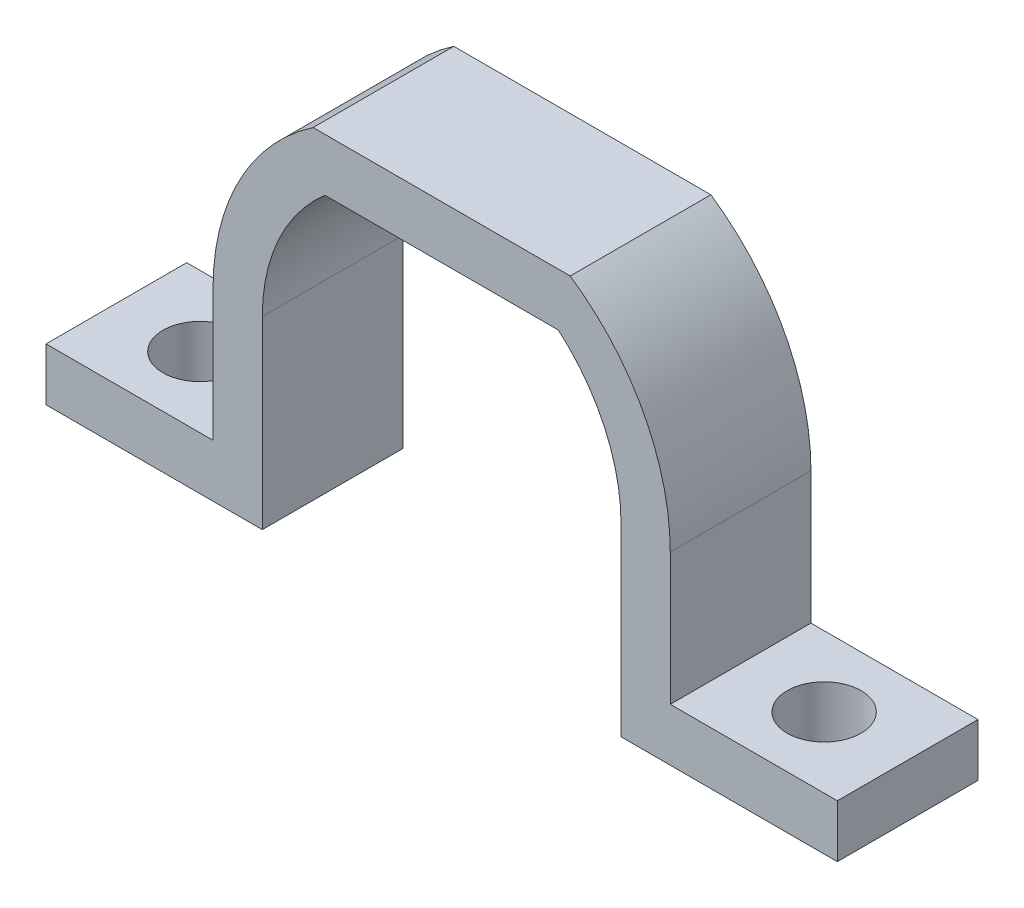
SolidWorks part; units mm, degrees
ref_plane "Front Plane" through (0, 0, 0) normal (0, 0, 1) x (1, 0, 0)
ref_plane "Top Plane" through (0, 0, 0) normal (0, 1, 0) x (1, 0, 0)
ref_plane "Right Plane" through (0, 0, 0) normal (1, 0, 0) x (0, 0, -1)
sketch "Sketch1" plane through (0, 0, 0) normal (0, 0, 1) x (1, 0, 0)
  line L0 (-6.6316, 7.75) -> (6.6316, 7.75)
  line L2 (-13, -7.5) -> (-22.5, -7.5)
  line L3 (-22.5, -7.5) -> (-22.5, -10.5)
  line L4 (-22.5, -10.5) -> (-10.2, -10.5)
  line L5 (22.5, -10.5) -> (22.5, -7.5)
  line L7 (13, -7.5) -> (22.5, -7.5)
  line L8 (-7.3101, 10.75) -> (7.3101, 10.75)
  line L9 (-13, 0) -> (-13, -7.5)
  line L10 (13, 0) -> (13, -7.5)
  line L12 (-10.2, 0) -> (-10.2, -10.5)
  line L13 (10.2, 0) -> (10.2, -10.5)
  line L14 (10.2, -10.5) -> (22.5, -10.5)
  arc A0 (-6.6316, 7.75) -> (-10.2, 0) centre (0, 0) ccw
  arc A1 (10.2, 0) -> (6.6316, 7.75) centre (0, 0) ccw
  arc A2 (-7.3101, 10.75) -> (-13, 0) centre (0, 0) ccw
  arc A3 (13, 0) -> (7.3101, 10.75) centre (0, 0) ccw
  dimension "D1" = 20.4
  dimension "D6" = 26
  dimension "D2" = 7.75
  dimension "D3" = 3
  dimension "D4" = 10.5
  dimension "D5" = 45
  dimension "D7" = 3
extrude "Clamp" add sketch "Sketch1" along normal blind 8
sketch "Sketch2" plane through (0, -7.5, 0) normal (0, 1, 0) x (1, 0, 0)
  line L0 (-22.5, -8) -> (-22.5, 0) construction
  line L1 (-13, 0) -> (-22.5, 0) construction
  line L2 (22.5, 0) -> (13, 0) construction
  circle A0 centre (-17.75, -4) radius 2.1
  circle A1 centre (17.75, -4) radius 2.1
  point P6 (-22.5, -4)
  point P9 (-17.75, 0)
  point P12 (17.75, 0)
  dimension "D1" = 4.2
extrude "Screw Hole" cut sketch "Sketch2" against normal through all
